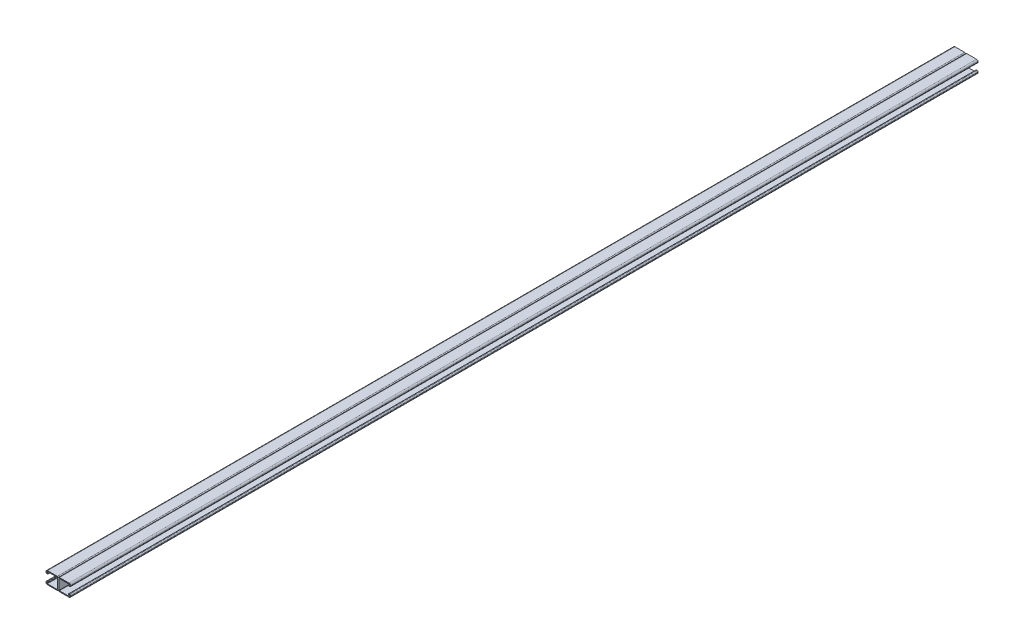
SolidWorks part; units mm, degrees
ref_plane "Front Plane" through (0, 0, 0) normal (0, 0, 1) x (1, 0, 0)
ref_plane "Top Plane" through (0, 0, 0) normal (0, 1, 0) x (1, 0, 0)
ref_plane "Right Plane" through (0, 0, 0) normal (1, 0, 0) x (0, 0, -1)
sketch "Sketch1" plane through (0, 0, 0) normal (0, 0, 1) x (1, 0, 0)
  line L0 (0, 0) -> (-41.275, 0) construction
  line L3 (-41.275, 20.6375) -> (0, 20.6375) construction
  line L4 (-41.275, 20.6375) -> (-41.275, -20.6375) construction
  line L5 (-41.275, -20.6375) -> (0, -20.6375) construction
  line L6 (0, 20.6375) -> (0, -20.6375) construction
  line L7 (-36.2267, 20.6375) -> (-3.4607, 20.6375)
  line L8 (0, 17.1767) -> (0, -17.1767)
  line L9 (-2.794, -17.1767) -> (-2.794, 17.1767)
  line L10 (-3.4608, 17.8435) -> (-36.2267, 17.8435)
  line L11 (-41.275, 15.5892) -> (-41.275, 14.5732)
  line L12 (-37.8142, 11.1125) -> (-35.5346, 11.1125)
  line L14 (-35.5346, 13.9065) -> (-37.8142, 13.9065)
  line L15 (-38.481, 14.5732) -> (-38.481, 15.5892)
  line L16 (-38.481, -14.5733) -> (-38.481, -15.5893)
  line L17 (-35.5346, -13.9065) -> (-37.8142, -13.9065)
  line L18 (-37.8142, -11.1125) -> (-35.5346, -11.1125)
  line L19 (-41.275, -15.5893) -> (-41.275, -14.5733)
  line L20 (-3.4607, -17.8435) -> (-36.2267, -17.8435)
  line L21 (-36.2267, -20.6375) -> (-3.4607, -20.6375)
  line L22 (-2.794, -20.6375) -> (-2.794, 20.6375) construction
  arc A1 (0, 17.1767) -> (-3.4607, 20.6375) centre (-3.4607, 17.1767) ccw
  arc A2 (-2.794, 17.1767) -> (-3.4608, 17.8435) centre (-3.4607, 17.1767) ccw
  arc A4 (-36.2267, 20.6375) -> (-41.275, 15.5892) centre (-36.2267, 15.5892) ccw
  arc A5 (-41.275, 14.5732) -> (-37.8142, 11.1125) centre (-37.8142, 14.5732) ccw
  arc A6 (-35.5346, 11.1125) -> (-35.5346, 13.9065) centre (-35.5346, 12.5095) ccw
  arc A7 (-37.8142, 13.9065) -> (-38.481, 14.5732) centre (-37.8142, 14.5732) cw
  arc A8 (-38.481, 15.5892) -> (-36.2267, 17.8435) centre (-36.2267, 15.5892) cw
  arc A9 (-38.481, -15.5893) -> (-36.2267, -17.8435) centre (-36.2267, -15.5893) ccw
  arc A10 (-37.8142, -13.9065) -> (-38.481, -14.5733) centre (-37.8142, -14.5733) ccw
  arc A11 (-35.5346, -11.1125) -> (-35.5346, -13.9065) centre (-35.5346, -12.5095) cw
  arc A12 (-41.275, -14.5733) -> (-37.8142, -11.1125) centre (-37.8142, -14.5733) cw
  arc A13 (-36.2267, -20.6375) -> (-41.275, -15.5893) centre (-36.2267, -15.5893) cw
  arc A14 (-2.794, -17.1767) -> (-3.4607, -17.8435) centre (-3.4607, -17.1767) cw
  arc A15 (0, -17.1767) -> (-3.4607, -20.6375) centre (-3.4607, -17.1767) cw
  point P24 (0, 20.6375)
  point P65 (-2.794, 0)
  dimension "D1" = 3.4608
  dimension "D2" = 5.0482
  dimension "D3" = 3.4608
  dimension "Ht." = 41.275
  dimension "Wd." = 41.275
  dimension "Thk." = 2.794
  dimension "D4" = 9.525
  dimension "D5" = 7.1374
extrude "Boss-Extrude1" add sketch "Sketch1" against normal blind 3048
sketch "Sketch3" plane through (0, 0, 0) normal (1, 0, 0) x (0, 0, -1)
  line L0 (0, 0) -> (3048, 0) construction
  point P2 (101.6, 0)
  point P3 (2946.4, 0)
  dimension "D1" = 101.6
  dimension "D2" = 101.6
  dimension "D3" = 3048
mirror "Mirror1" about plane through (0, 17.1767, -3048) normal (1, 0, 0) of bodies 114
combine bodies "Combine1" operation type add bodies to combine 117 114
equation "\"D3@Sketch3\" = \"Lg.@Boss-Extrude1\""
